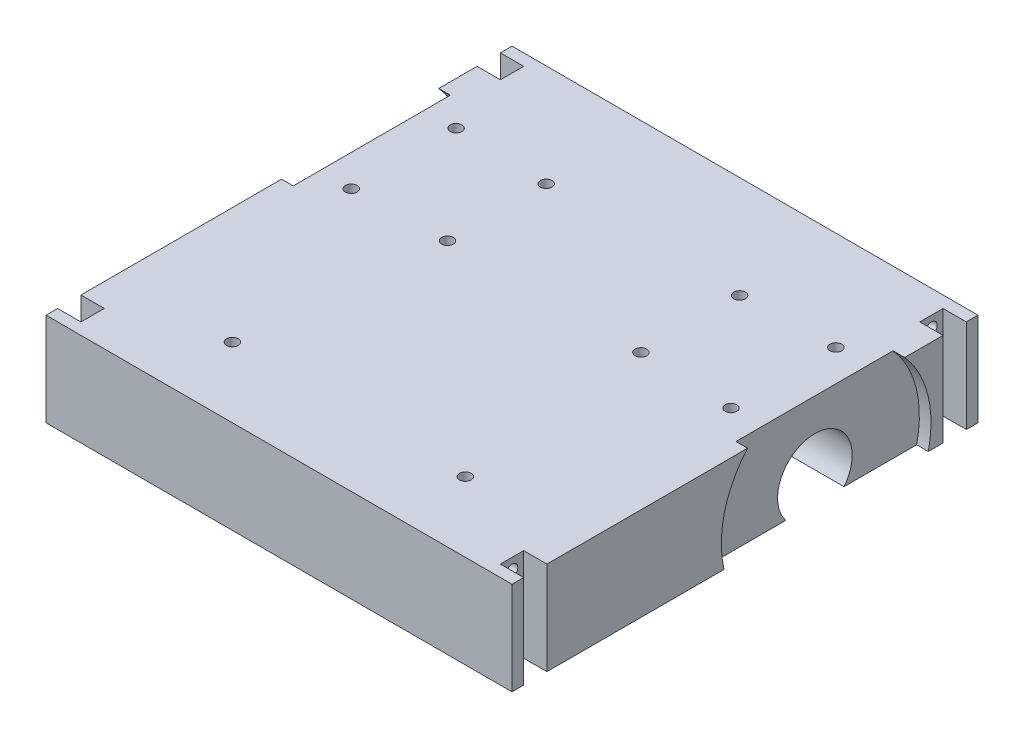
SolidWorks part; units mm, degrees
ref_plane "Plan de face" through (0, 0, 0) normal (0, 0, 1) x (1, 0, 0)
ref_plane "Plan de dessus" through (0, 0, 0) normal (0, 1, 0) x (1, 0, 0)
ref_plane "Plan de droite" through (0, 0, 0) normal (1, 0, 0) x (0, 0, -1)
sketch "Esquisse2" plane through (0, 0, 0) normal (0, 1, 0) x (1, 0, 0)
  line L1 (100, 100) -> (-100, 100)
  line L2 (100, 100) -> (100, -100)
  line L3 (100, -100) -> (-100, -100)
  line L4 (-100, 100) -> (-100, -100)
  line L5 (100, 100) -> (-100, -100) construction
  line L6 (100, -100) -> (-100, 100) construction
  point P0 (0, 0)
  dimension "D1" = 200
  dimension "D2" = 200
extrude "BASE" add sketch "Esquisse2" along normal blind 40
sketch "Esquisse3" plane through (100, 0, 0) normal (1, 0, 0) x (0, 0, -1)
  line L0 (100, 10) -> (-1.4225, 10) construction
  line L1 (100, 40) -> (100, 0) construction
  line L2 (-100, 0) -> (100, 0) construction
  circle A0 centre (35, 10) radius 15
  point P4 (35, 10)
  dimension "D3" = 30
  dimension "D1" = 65
  dimension "D2" = 10
extrude "BLOC MOTEUR 1." cut sketch "Esquisse3" against normal blind 80
sketch "Esquisse4" plane through (0, 0, 0) normal (0, -1, 0) x (1, 0, 0)
  line L0 (20, -46.1803) -> (100, -46.1803) construction
  line L1 (20, -23.8197) -> (30, -23.8197)
  line L2 (20, -23.8197) -> (20, -46.1803)
  line L3 (20, -46.1803) -> (30, -46.1803)
  line L4 (30, -23.8197) -> (30, -46.1803)
  dimension "D1" = 10
extrude "ACCES MOTEUR" cut sketch "Esquisse4" against normal blind 37
ref_plane "PLAN SYM " through (0, 0, 0) normal (1, 0, 0) x (0, 0, -1)
sketch "Esquisse6" plane through (100, 0, 0) normal (1, 0, 0) x (0, 0, -1)
  line L0 (20, 10) -> (50, 10) construction
  arc A0 (23.8197, 20) -> (23.8197, 0) centre (35, 10) ccw construction
  arc A1 (46.1803, 0) -> (23.8197, 0) centre (35, 10) ccw construction
  circle A2 centre (35, 10) radius 16.01
  dimension "D1" = 32.02
extrude "BLOC MOTEUR 2" cut sketch "Esquisse6" against normal blind 37
mirror "SYM BLOC MOTEUR" about plane through (0, 0, 0) normal (1, 0, 0) of "ACCES MOTEUR", "BLOC MOTEUR 1.", "BLOC MOTEUR 2"
sketch "Esquisse7" plane through (0, 0, 0) normal (0, -1, 0) x (1, 0, 0)
  line L0 (-81.5, -22.4972) -> (-81.5, -57.5028) construction
  line L1 (-100, -22.4972) -> (-63, -22.4972) construction
  line L2 (-41.5, -23.8197) -> (-41.5, -67.469) construction
  line L3 (-63, -23.8197) -> (-20, -23.8197) construction
  line L4 (-63, -47.5028) -> (-100, -47.5028) construction
  line L5 (-20, -46.1803) -> (-63, -46.1803) construction
  line L6 (-81.5, -22.4972) -> (-81.5, -13.9891) construction
  line L7 (-41.5, -56.1803) -> (-41.5, -20.9291) construction
  circle A0 centre (-81.5, -12.4972) radius 2.5
  circle A1 centre (-41.5, -13.8197) radius 2.5
  circle A2 centre (-41.5, -56.1803) radius 2.5
  circle A3 centre (-81.5, -57.5028) radius 2.5
  point P8 (-81.5, -12.4972)
  point P9 (-81.5, -57.5028)
  point P10 (-41.5, -56.1803)
  point P11 (-41.5, -13.8197)
  dimension "D5" = 5
  dimension "D6" = 5
  dimension "D7" = 5
  dimension "D8" = 5
  dimension "D1" = 10
  dimension "D2" = 10
  dimension "D3" = 10
  dimension "D4" = 10
extrude "VIS MOTEUR" cut sketch "Esquisse7" against normal through all
mirror "SYM VIS" about plane through (0, 0, 0) normal (1, 0, 0) of "VIS MOTEUR"
sketch "Esquisse8" plane through (100, 0, 0) normal (1, 0, 0) x (0, 0, -1)
  line L0 (35, 26.01) -> (35, -8.48) construction
  line L1 (22.4972, 0) -> (47.1653, 20.408) construction
  arc A0 (47.5028, 0) -> (22.4972, 0) centre (35, 10) ccw construction
  circle A1 centre (34.8312, 10.204) radius 45
  dimension "D1" = 90
extrude "VIDE ROUE" cut sketch "Esquisse8" against normal blind 5
sketch "Esquisse9" plane through (100, 0, 0) normal (1, 0, 0) x (0, 0, -1)
  line L0 (78.6591, 0) -> (100, 0) construction
  line L1 (95, 40) -> (85, 40)
  line L2 (95, 40) -> (95, 0)
  line L3 (95, 0) -> (85, 0)
  line L4 (85, 40) -> (85, 0)
  line L5 (-100, 0) -> (-8.9966, 0) construction
  line L6 (-95, 40) -> (-85, 40)
  line L7 (-95, 40) -> (-95, 0)
  line L8 (-95, 0) -> (-85, 0)
  line L9 (-85, 40) -> (-85, 0)
  line L10 (-100, 40) -> (-100, 0) construction
  line L11 (100, 40) -> (100, 0) construction
  line L12 (-100, 40) -> (1.1089, 40) construction
  line L13 (68.5536, 40) -> (100, 40) construction
  dimension "D1" = 10
  dimension "D2" = 10
  dimension "D3" = 5
  dimension "D4" = 5
extrude "VIDE GUIDAGE TIGE" cut sketch "Esquisse9" against normal blind 10
sketch "Esquisse10" plane through (90, 0, 0) normal (1, 0, 0) x (0, 0, -1)
  line L0 (-95, 40) -> (-85, 0) construction
  line L1 (-90, 40) -> (-90, 0) construction
  line L2 (-85, 40) -> (-95, 40) construction
  line L3 (-95, 0) -> (-85, 0) construction
  line L4 (0, 0) -> (0, 47.1044) construction
  circle A0 centre (-90, 35) radius 2.5
  circle A1 centre (-90, 25) radius 2.5
  circle A2 centre (90, 25) radius 2.5
  circle A3 centre (90, 35) radius 2.5
  circle A4 centre (-90, 15) radius 2.5
  circle A5 centre (90, 15) radius 2.5
  dimension "D2" = 5
  dimension "D3" = 5
  dimension "D5" = 5
  dimension "D1" = 5
  dimension "D4" = 10
  dimension "D6" = 10
extrude "TROU VIS" cut sketch "Esquisse10" against normal blind 100
mirror "SYM - ROUE - TIGE" about plane through (0, 0, 0) normal (1, 0, 0) of "VIDE ROUE", "VIDE GUIDAGE TIGE", "TROU VIS"
sketch "Esquisse11" plane through (0, 0, 0) normal (0, -1, 0) x (1, 0, 0)
  line L0 (-100, 8.9966) -> (-100, 85) construction
  line L1 (-100, 100) -> (100, 100) construction
  line L2 (0, -11.3509) -> (0, 25.1807) construction
  circle A0 centre (-50, 70) radius 2.5
  circle A1 centre (50, 70) radius 2.5
  point P0 (-50, 70)
  point P1 (198.053, 81.8045)
  dimension "D3" = 5
  dimension "D1" = 50
  dimension "D2" = 30
extrude "VIDE PATIN" cut sketch "Esquisse11" against normal through all
